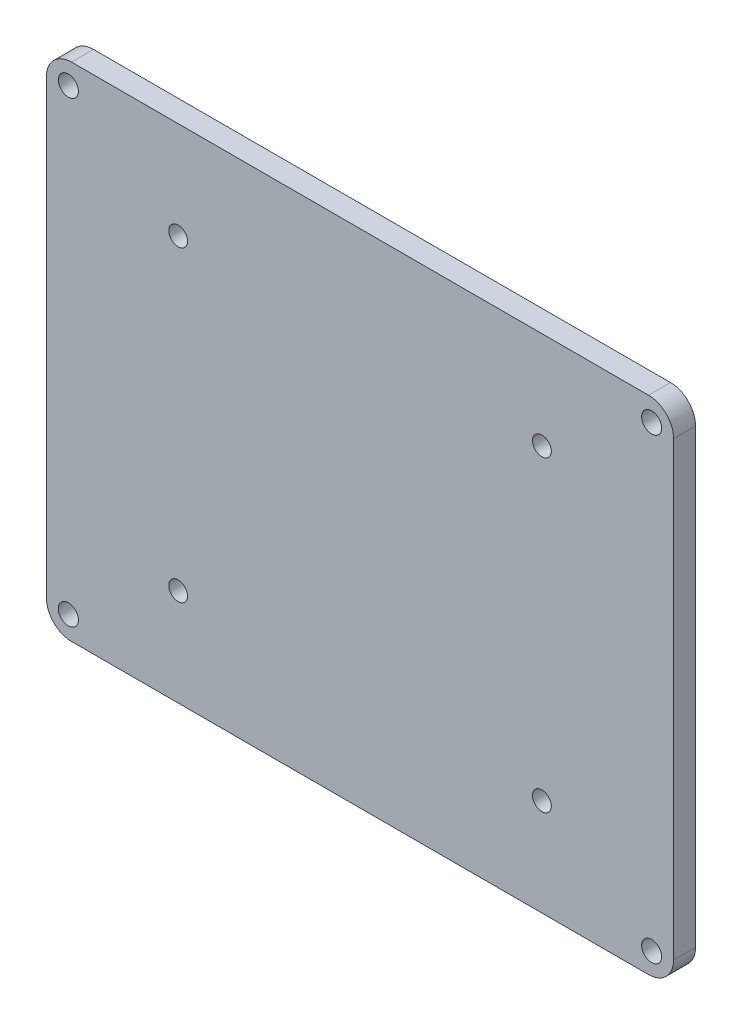
SolidWorks part; units mm, degrees
ref_plane "Front Plane" through (0, 0, 0) normal (0, 0, 1) x (1, 0, 0)
ref_plane "Top Plane" through (0, 0, 0) normal (0, 1, 0) x (1, 0, 0)
ref_plane "Right Plane" through (0, 0, 0) normal (1, 0, 0) x (0, 0, -1)
sketch "Sketch2" plane through (0, 0, 0) normal (0, 0, 1) x (1, 0, 0)
  line L0 (0, 0) -> (0, 36.5) construction
  line L1 (-46, -40) -> (46, -40)
  line L2 (-50, -36) -> (-50, 36)
  line L3 (-46, 40) -> (46, 40)
  line L4 (50, -36) -> (50, 36)
  line L5 (-50, -40) -> (50, 40) construction
  line L6 (-50, 40) -> (50, -40) construction
  line L7 (0, 36.5) -> (-46.5, 36.5) construction
  line L8 (0, 36.5) -> (46.5, 36.5) construction
  line L9 (0, 0) -> (0, -36.5) construction
  line L10 (0, -36.5) -> (46.5, -36.5) construction
  line L11 (0, -36.5) -> (-46.5, -36.5) construction
  arc A0 (50, 36) -> (46, 40) centre (46, 36) ccw
  arc A1 (46, -40) -> (50, -36) centre (46, -36) ccw
  arc A2 (-46, -40) -> (-50, -36) centre (-46, -36) cw
  arc A3 (-50, 36) -> (-46, 40) centre (-46, 36) cw
  circle A4 centre (-46.5, 36.5) radius 1.6
  circle A5 centre (46.5, 36.5) radius 1.6
  circle A6 centre (-46.5, -36.5) radius 1.6
  circle A7 centre (46.5, -36.5) radius 1.6
  point P0 (0, 0)
  dimension "D3" = 4
  dimension "D6" = 3.2
  dimension "D7" = 46.5
  dimension "D8" = 3.2
  dimension "D10" = 3.2
  dimension "D11" = 3.2
  dimension "D1" = 80
  dimension "D2" = 100
  dimension "D4" = 36.5
  dimension "D5" = 46.5
  dimension "D9" = 36.5
extrude "Boss-Extrude1" add sketch "Sketch2" along normal blind 3.5
ref_plane "Plane1" through (0, 0, 3.5) normal (0, 0, 1) x (1, 0, 0)
sketch "Sketch3" plane through (0, 0, 3.5) normal (0, 0, 1) x (1, 0, 0)
  line L5 (29, -24.5) -> (-29, 24.5) construction
  line L6 (29, 24.5) -> (-29, -24.5) construction
  circle A0 centre (-29, 24.5) radius 1.5
  circle A1 centre (-29, -24.5) radius 1.5
  circle A2 centre (29, -24.5) radius 1.5
  circle A3 centre (29, 24.5) radius 1.5
  point P0 (0, 0)
  dimension "D3" = 3
  dimension "D4" = 3
  dimension "D5" = 3
  dimension "D6" = 3
  dimension "D1" = 58
  dimension "D2" = 49
extrude "Cut-Extrude1" cut sketch "Sketch3" against normal blind 8
